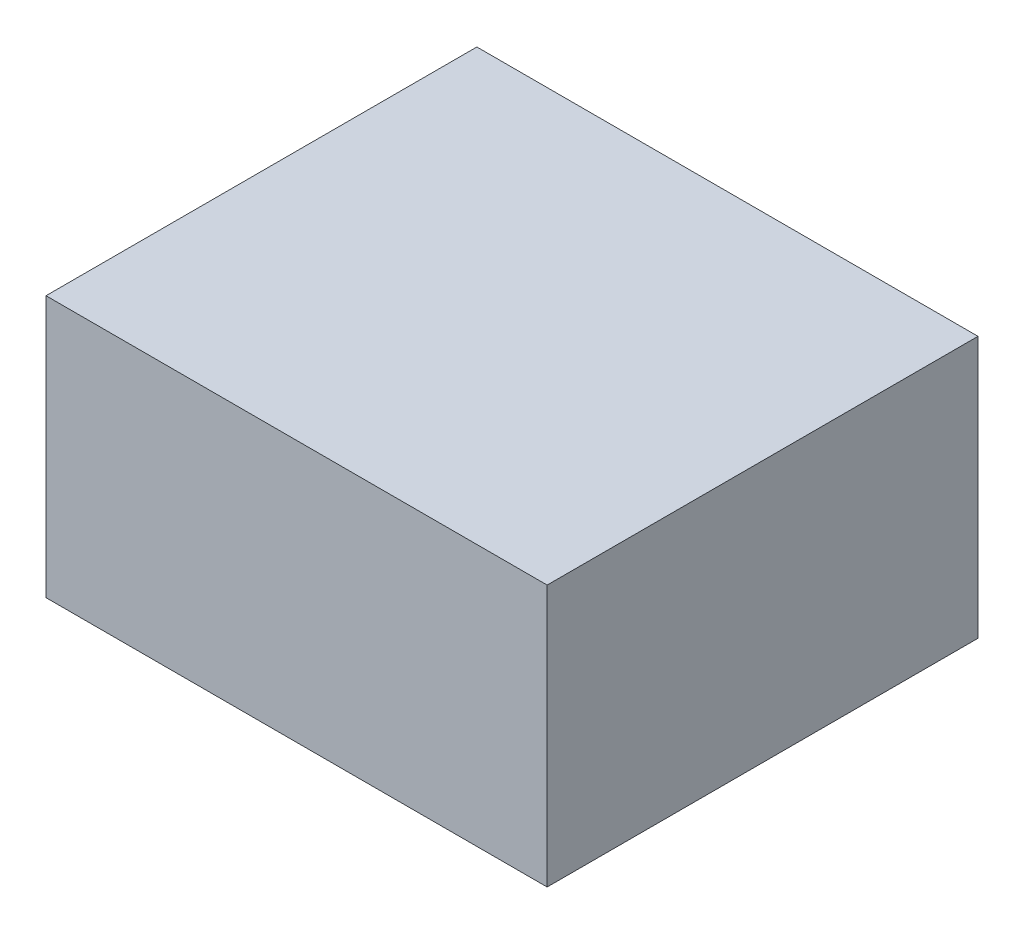
SolidWorks part; units mm, degrees
ref_plane "Front Plane" through (0, 0, 0) normal (0, 0, 1) x (1, 0, 0)
ref_plane "Top Plane" through (0, 0, 0) normal (0, 1, 0) x (1, 0, 0)
ref_plane "Right Plane" through (0, 0, 0) normal (1, 0, 0) x (0, 0, -1)
sketch "Sketch1" plane through (0, 0, 0) normal (0, 0, 1) x (1, 0, 0)
  line L0 (12.2428, -3.81) -> (-1.7272, -3.81)
  line L1 (-1.7272, -3.81) -> (-1.7272, 3.48)
  line L2 (-1.7272, 3.48) -> (12.2428, 3.48)
  line L3 (12.2428, 3.48) -> (12.2428, -3.81)
extrude "Component_Outline" add sketch "Sketch1" along normal blind 12.01 separate body
sketch3d "3DSketch1"
  line L0 (0, 0, 0) -> (1, 0, 0)
  line L1 (0, 0, 0) -> (0, 1, 0)
  line L2 (0, 0, 0) -> (0, 0, 1)
  point P0 (0, 0, 0)
